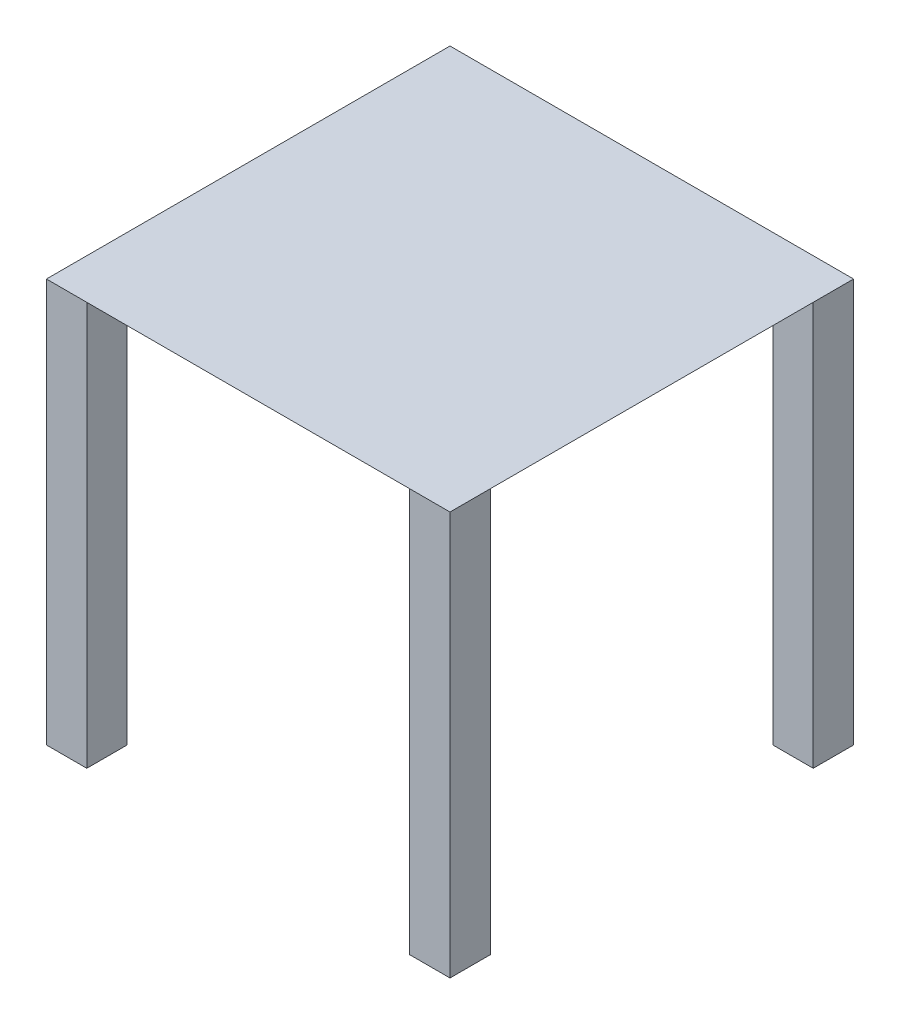
SolidWorks part; units mm, degrees
ref_plane "Front Plane" through (0, 0, 0) normal (0, 0, 1) x (1, 0, 0)
ref_plane "Top Plane" through (0, 0, 0) normal (0, 1, 0) x (1, 0, 0)
ref_plane "Right Plane" through (0, 0, 0) normal (1, 0, 0) x (0, 0, -1)
sketch "Sketch1" plane through (0, 0, 0) normal (0, 1, 0) x (1, 0, 0)
  line L1 (-500, -500) -> (500, -500)
  line L2 (-500, -500) -> (-500, 500)
  line L3 (-500, 500) -> (500, 500)
  line L4 (500, -500) -> (500, 500)
  line L5 (-500, -500) -> (500, 500) construction
  line L6 (-500, 500) -> (500, -500) construction
  point P0 (0, 0)
  dimension "D1" = 1000
  dimension "D2" = 1000
ref_plane "Plane1" through (0, -400, 0) normal (0, -1, 0) x (-1, 0, 0)
sketch "Sketch2" plane through (0, -400, 0) normal (0, -1, 0) x (-1, 0, 0)
  point P0 (0, 0)
loft "Loft1" add profiles "Sketch1", "Sketch2"
sketch "Sketch5" plane through (0, -400, 0) normal (0, -1, 0) x (-1, 0, 0)
  line L0 (500, 500) -> (0, 0) construction
  line L1 (-75, -75) -> (75, -75)
  line L2 (-75, -75) -> (-75, 75)
  line L3 (-75, 75) -> (75, 75)
  line L4 (75, -75) -> (75, 75)
  line L5 (-75, -75) -> (75, 75) construction
  line L6 (-75, 75) -> (75, -75) construction
  point P0 (0, 0)
  dimension "D1" = 150
  dimension "D2" = 150
extrude "Cut-Extrude1" cut sketch "Sketch5" against normal blind 100
sketch "Sketch6" plane through (0, 0, 0) normal (0, 1, 0) x (1, 0, 0)
  line L1 (-500, 500) -> (-400, 500)
  line L2 (-500, 500) -> (-500, 400)
  line L3 (-500, 400) -> (-400, 400)
  line L4 (-400, 500) -> (-400, 400)
  line L5 (500, 500) -> (400, 500)
  line L6 (500, 500) -> (500, 400)
  line L7 (500, 400) -> (400, 400)
  line L8 (400, 500) -> (400, 400)
  line L9 (-500, -500) -> (-400, -500)
  line L10 (-500, -500) -> (-500, -400)
  line L11 (-500, -400) -> (-400, -400)
  line L12 (-400, -500) -> (-400, -400)
  line L13 (500, -500) -> (400, -500)
  line L14 (500, -500) -> (500, -400)
  line L15 (500, -400) -> (400, -400)
  line L16 (400, -500) -> (400, -400)
  dimension "D1" = 100
  dimension "D2" = 100
  dimension "D3" = 100
  dimension "D4" = 100
  dimension "D5" = 100
  dimension "D6" = 100
  dimension "D7" = 100
  dimension "D8" = 100
extrude "Boss-Extrude1" add sketch "Sketch6" against normal blind 1000
sketch "Sketch7" plane through (0, -400, 0) normal (0, -1, 0) x (-1, 0, 0)
  line L1 (-75, 75) -> (75, 75)
  line L2 (-75, 75) -> (-75, -75)
  line L3 (-75, -75) -> (75, -75)
  line L4 (75, 75) -> (75, -75)
  dimension "D1" = 150
ref_plane "Plane8" through (75, -340, 75) normal (1, 0, 0) x (0, 0, -1)
